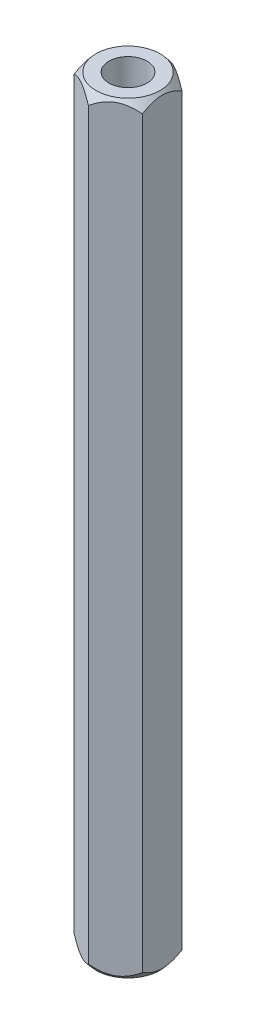
SolidWorks part; units mm, degrees
ref_plane "Front Plane" through (0, 0, 0) normal (0, 0, 1) x (1, 0, 0)
ref_plane "Top Plane" through (0, 0, 0) normal (0, 1, 0) x (1, 0, 0)
ref_plane "Right Plane" through (0, 0, 0) normal (1, 0, 0) x (0, 0, -1)
sketch "Sketch1" plane through (0, 0, 0) normal (0, 1, 0) x (1, 0, 0)
  line L1 (0, 2.5981) -> (-2.25, 1.299)
  line L2 (-2.25, 1.299) -> (-2.25, -1.299)
  line L3 (-2.25, -1.299) -> (0, -2.5981)
  line L4 (0, -2.5981) -> (2.25, -1.299)
  line L5 (2.25, -1.299) -> (2.25, 1.299)
  line L6 (2.25, 1.299) -> (0, 2.5981)
  circle A0 centre (0, 0) radius 2.25 construction
  circle A1 centre (0, 0) radius 1.25
  dimension "D1" = 4.5
  dimension "D2" = 2.5
extrude "Boss-Extrude1" add sketch "Sketch1" along normal blind 50
sketch "Sketch2" plane through (0, 0, 0) normal (1, 0, 0) x (0, 0, -1)
  line L0 (-2.0981, 50) -> (-2.5981, 49.4)
  line L1 (-2.5981, 50) -> (-2.5981, 0) construction
  line L2 (-2.5981, 49.4) -> (-2.5981, 50)
  line L3 (-2.5981, 50) -> (-2.0981, 50)
  line L5 (0, 50) -> (0, 49.0924) construction
  line L6 (-1.299, 50) -> (1.299, 50) construction
  dimension "D1" = 0.6
  dimension "D2" = 0.5
revolve "Cut-Revolve1" cut sketch "Sketch2" angle 360 about L5
ref_plane "Plane1" through (0, 25, 0) normal (0, 1, 0) x (1, 0, 0)
mirror "Mirror1" about plane through (0, 25, 0) normal (0, 1, 0) of "Cut-Revolve1"
